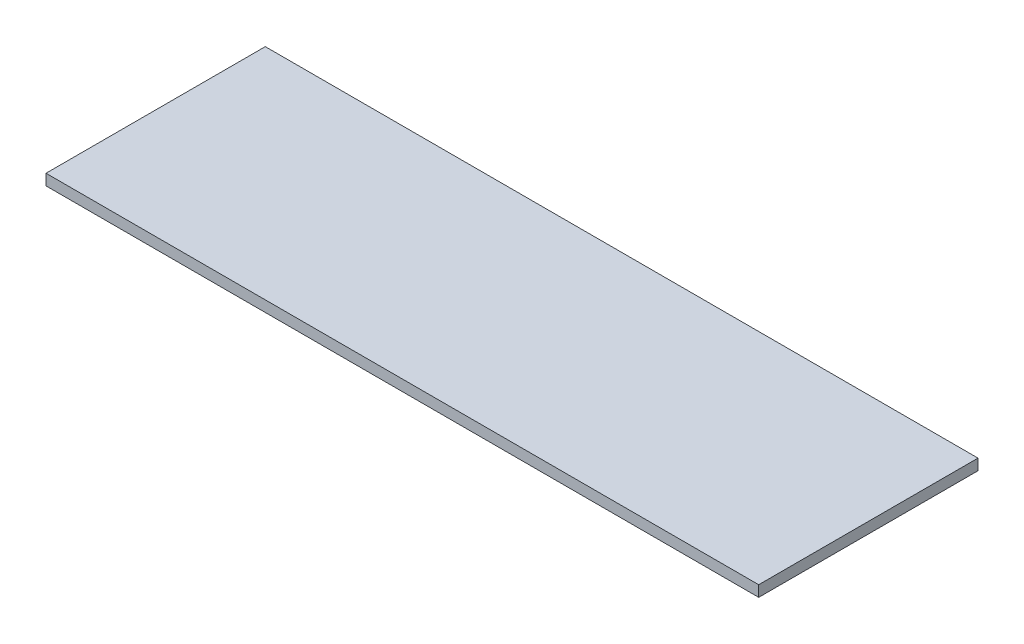
SolidWorks part; units mm, degrees
ref_plane "Alzado" through (0, 0, 0) normal (0, 0, 1) x (1, 0, 0)
ref_plane "Planta" through (0, 0, 0) normal (0, 1, 0) x (1, 0, 0)
ref_plane "Vista lateral" through (0, 0, 0) normal (1, 0, 0) x (0, 0, -1)
sketch "Croquis1" plane through (0, 0, 0) normal (0, 1, 0) x (1, 0, 0)
  line L1 (-585, 180) -> (585, 180)
  line L2 (-585, 180) -> (-585, -180)
  line L3 (-585, -180) -> (585, -180)
  line L4 (585, 180) -> (585, -180)
  line L5 (-585, 180) -> (585, -180) construction
  line L6 (-585, -180) -> (585, 180) construction
  point P0 (0, 0)
  dimension "D1" = 1170
  dimension "D2" = 360
extrude "Saliente-Extruir1" add sketch "Croquis1" along normal blind 18
